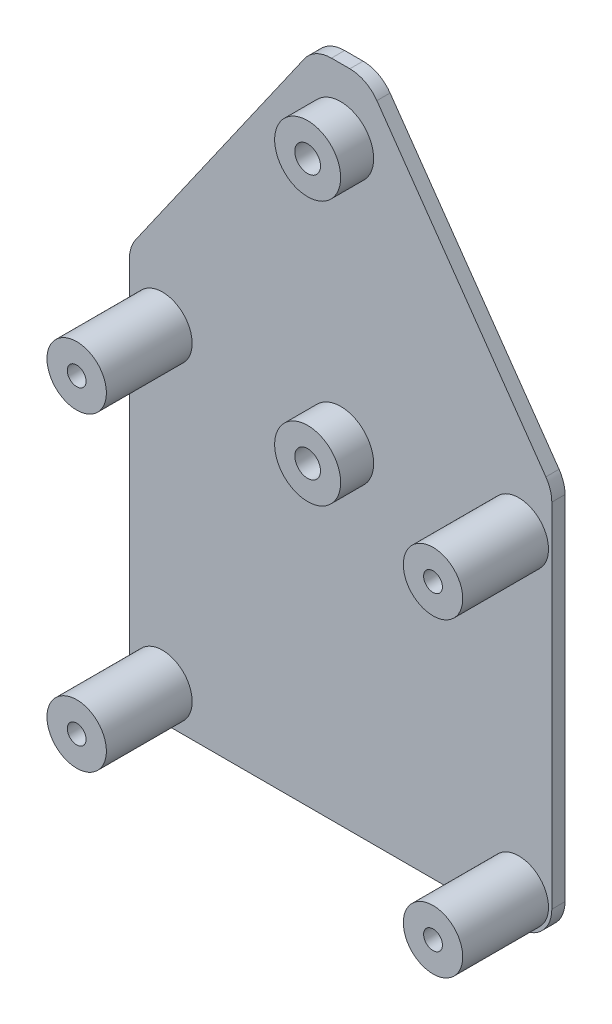
SolidWorks part; units mm, degrees
ref_plane "Front Plane" through (0, 0, 0) normal (1, 0, 0) x (0, 1, 0)
ref_plane "Top Plane" through (0, 0, 0) normal (0, 0, 1) x (0, 1, 0)
ref_plane "Right Plane" through (0, 0, 0) normal (0, 1, 0) x (-1, 0, 0)
sketch "Sketch1" plane through (0, 0, 0) normal (0, 0, 1) x (0, 1, 0)
  line L0 (100, 32) -> (0, 32) construction
  line L1 (0, 0) -> (100, 0)
  line L2 (0, 0) -> (0, 64)
  line L3 (0, 64) -> (100, 64)
  line L4 (100, 0) -> (100, 64)
  circle A0 centre (90, 32) radius 1.95
  circle A1 centre (50, 32) radius 1.95
  point P13 (5.0832, 25.0544)
  dimension "D5" = 3.9
  dimension "D1" = 64
  dimension "D2" = 100
  dimension "D3" = 40
  dimension "D4" = 50
extrude "Boss-Extrude1" add sketch "Sketch1" along normal blind 2
sketch "Sketch2" plane through (0, 0, 2) normal (0, 0, 1) x (1, 0, 0)
  circle A0 centre (-32, 50) radius 5
  circle A1 centre (-32, 50) radius 1.95
  circle A2 centre (-32, 90) radius 5
  circle A3 centre (-32, 90) radius 1.95
  dimension "D1" = 10
extrude "Boss-Extrude2" add sketch "Sketch2" along normal blind 5
sketch "Sketch3" plane through (0, 0, 2) normal (0, 0, 1) x (1, 0, 0)
  line L0 (-32, 0) -> (-32, 100) construction
  line L1 (-64, 0) -> (0, 0) construction
  line L2 (0, 100) -> (-64, 100) construction
  line L3 (-59, 5) -> (-5, 5) construction
  line L4 (-59, 52) -> (-5, 52) construction
  circle A0 centre (-59, 5) radius 4.5
  circle A1 centre (-5, 5) radius 4.5
  circle A2 centre (-5, 52) radius 4.5
  circle A3 centre (-59, 52) radius 4.5
  circle A4 centre (-59, 52) radius 1.425
  circle A5 centre (-5, 52) radius 1.425
  circle A6 centre (-5, 5) radius 1.425
  circle A7 centre (-59, 5) radius 1.425
  point P9 (-32, 5)
  point P12 (-32, 52)
  dimension "D5" = 9
  dimension "D6" = 2.85
  dimension "D1" = 54
  dimension "D2" = 54
  dimension "D3" = 5
  dimension "D4" = 47
extrude "Boss-Extrude3" add sketch "Sketch3" along normal blind 13
sketch "Sketch4" plane through (0, 0, 2) normal (0, 0, 1) x (1, 0, 0)
  line L0 (-64, 100) -> (-36, 100)
  line L1 (0, 100) -> (-64, 100) construction
  line L2 (-36, 100) -> (-64, 60)
  line L3 (-64, 100) -> (-64, 0) construction
  line L4 (-64, 60) -> (-64, 100)
  line L5 (-28, 100) -> (0, 100)
  line L6 (0, 100) -> (0, 60)
  line L7 (0, 0) -> (0, 100) construction
  line L8 (0, 60) -> (-28, 100)
  dimension "D1" = 28
  dimension "D2" = 28
  dimension "D3" = 40
  dimension "D4" = 40
extrude "Cut-Extrude1" cut sketch "Sketch4" against normal through all
fillet "Fillet1" radius 5 6 edges at (-64, 0, 1) (-64, 60, 1) (-36, 100, 1) (-28, 100, 1) (0, 0, 1) (0, 60, 1)
